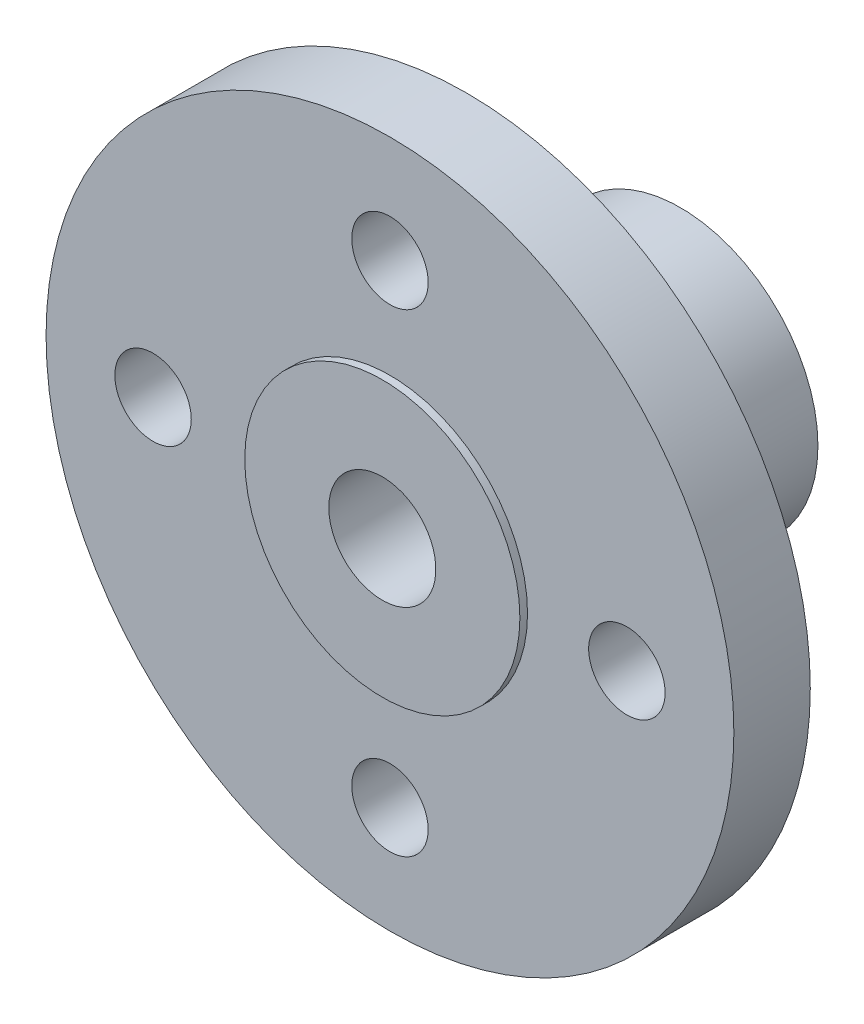
SolidWorks part; units mm, degrees
ref_plane "Front Plane" through (0, 0, 0) normal (0, 0, 1) x (1, 0, 0)
ref_plane "Top Plane" through (0, 0, 0) normal (0, 1, 0) x (1, 0, 0)
ref_plane "Right Plane" through (0, 0, 0) normal (1, 0, 0) x (0, 0, -1)
sketch "Sketch1" plane through (0, 0, 0) normal (0, 0, 1) x (1, 0, 0)
  line L0 (0, 9) -> (0, 3.4) construction
  circle A0 centre (0, 0) radius 9
  circle A1 centre (0, 0) radius 3.4
  circle A2 centre (0, 6.2) radius 1
  circle A3 centre (6.2, 0) radius 1
  circle A4 centre (0, -6.2) radius 1
  circle A5 centre (-6.2, 0) radius 1
  point P8 (0, 6.2)
  point P17 (0, 0)
  dimension "D1" = 18
  dimension "D2" = 6.8
  dimension "D3" = 2
  dimension "D4" = 4
extrude "Boss-Extrude1" add sketch "Sketch1" along normal blind 2
sketch "Sketch2" plane through (0, 0, 0) normal (0, 0, -1) x (-1, 0, 0)
  circle A0 centre (0, 0) radius 3.6
  circle A1 centre (0, 0) radius 1.4
  dimension "D1" = 2.8
  dimension "D2" = 7.2
extrude "Boss-Extrude2" add sketch "Sketch2" along normal blind 5.6 and the other way blind 2.2
sketch "Sketch3" plane through (0, 0, -5.6) normal (0, 0, -1) x (-1, 0, 0)
  circle A0 centre (0, 0) radius 2.75
  dimension "D1" = 5.5
extrude "Cut-Extrude1" cut sketch "Sketch3" against normal up to surface (5.6 mm away) up to face at (3.6, 0, 0)
